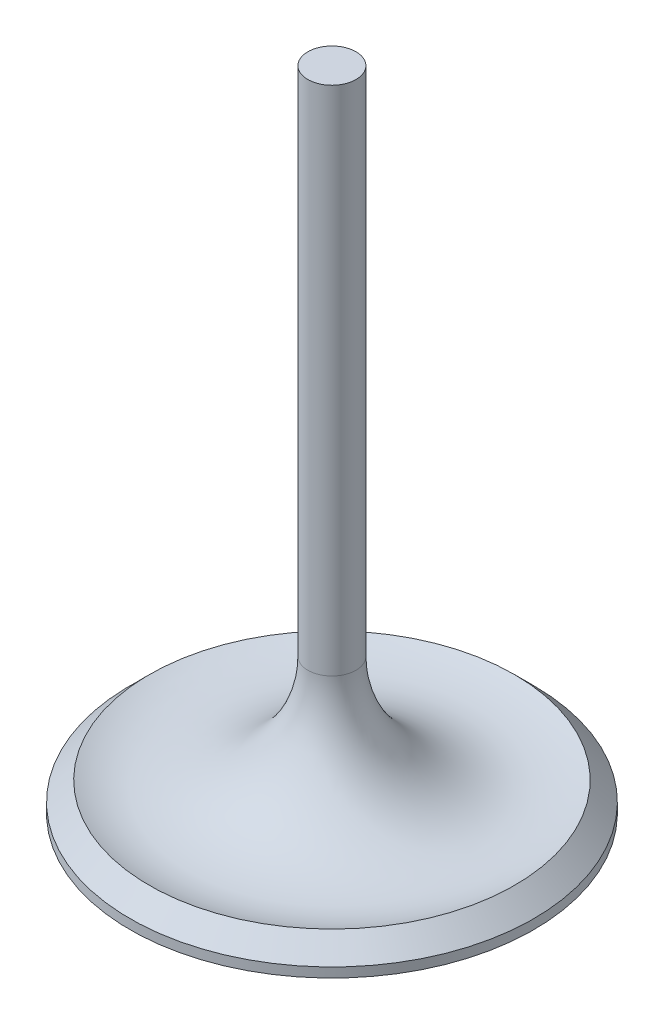
SolidWorks part; units mm, degrees
ref_plane "Front Plane" through (0, 0, 0) normal (0, 0, 1) x (1, 0, 0)
ref_plane "Top Plane" through (0, 0, 0) normal (0, 1, 0) x (1, 0, 0)
ref_plane "Right Plane" through (0, 0, 0) normal (1, 0, 0) x (0, 0, -1)
sketch "Sketch1" plane through (0, 0, 0) normal (0, 0, 1) x (1, 0, 0)
  line L0 (0, 0) -> (0, 85.55)
  line L1 (0, 85.55) -> (3.18, 85.55)
  line L2 (3.18, 85.55) -> (3.18, 17.9547)
  line L3 (0, 0) -> (26.67, 0)
  line L4 (26.67, 0) -> (26.67, 1.27)
  line L5 (26.67, 1.27) -> (24.13, 3.81)
  arc A0 (3.18, 17.9547) -> (24.13, 3.81) centre (18.43, 17.9547) ccw
  dimension "D7" = 15.25
  dimension "D1" = 85.55
  dimension "D2" = 3.18
  dimension "D3" = 26.67
  dimension "D4" = 1.27
  dimension "D5" = 3.81
  dimension "D6" = 45
revolve "Revolve1" add sketch "Sketch1" angle 360 about L0
